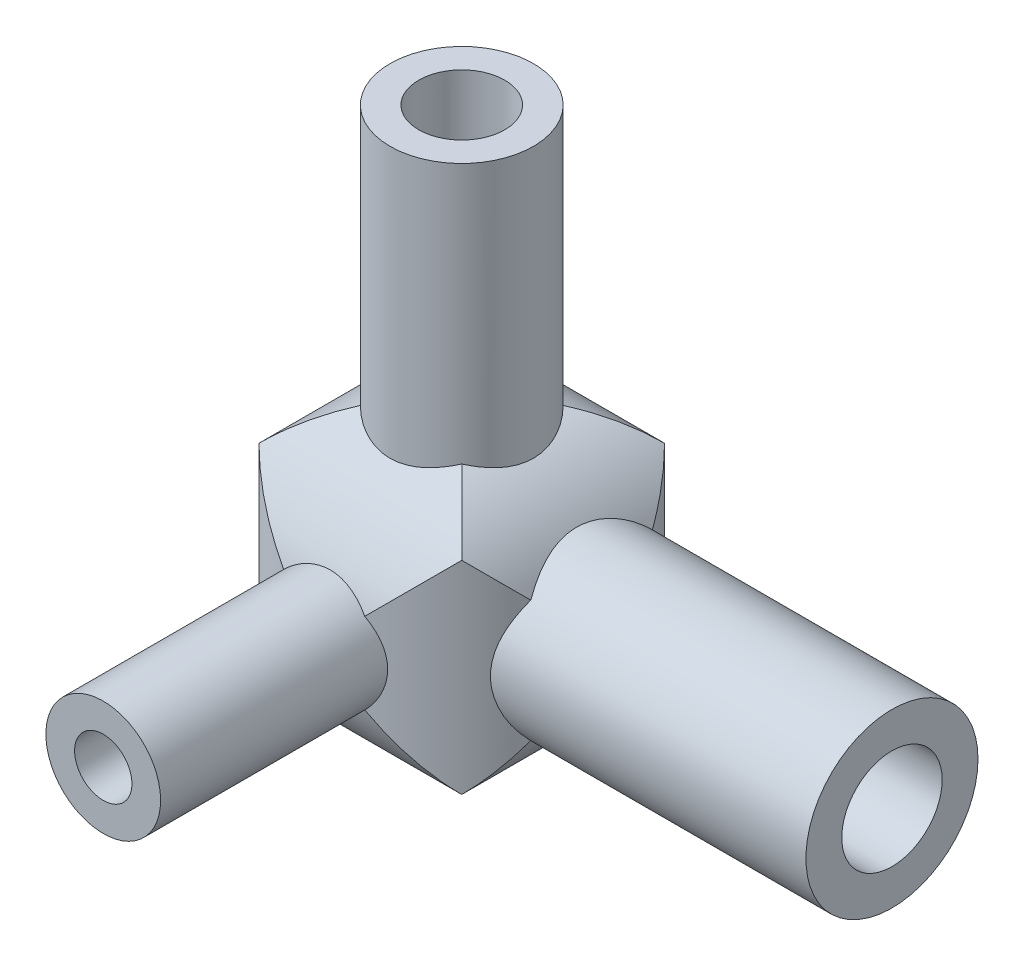
SolidWorks part; units mm, degrees
ref_plane "前视基准面" through (0, 0, 0) normal (0, 0, 1) x (1, 0, 0)
ref_plane "上视基准面" through (0, 0, 0) normal (0, 1, 0) x (1, 0, 0)
ref_plane "右视基准面" through (0, 0, 0) normal (1, 0, 0) x (0, 0, -1)
sketch3d "3D草图1"
  line L0 (-20, 0, 0) -> (20, 0, 0)
sweep "扫描2" add path "3D草图1" circular profile diameter 40 parameters "D3"=40
ref_plane "基准面1" through (0, -20, 0) normal (0, 1, 0) x (1, 0, 0)
sketch "草图2" plane through (0, -20, 0) normal (0, 1, 0) x (1, 0, 0)
  line L0 (-60, 60) -> (60, 60)
  line L1 (60, 60) -> (60, -60)
  line L2 (60, -60) -> (-60, -60)
  line L3 (-60, -60) -> (-60, 60)
  circle A0 centre (0, 0) radius 20
extrude "切除-拉伸1" cut sketch "草图2" along normal through all
ref_plane "基准面2" through (0, 0, -20) normal (0, 0, 1) x (1, 0, 0)
sketch "草图3" plane through (0, 0, -20) normal (0, 0, 1) x (1, 0, 0)
  line L0 (-60, -60) -> (60, -60)
  line L1 (60, -60) -> (60, 60)
  line L2 (60, 60) -> (-60, 60)
  line L3 (-60, 60) -> (-60, -60)
  circle A0 centre (0, 0) radius 20
extrude "切除-拉伸2" cut sketch "草图3" along normal through all
sketch3d "3D草图2"
  line L0 (-5, 0, 0) -> (60, 0, 0)
sweep "扫描4" add path "3D草图2" circular profile diameter 24 parameters "D3"=24
sketch3d "3D草图3"
  line L0 (0, -5, 0) -> (0, 55, 0)
sweep "扫描6" add path "3D草图3" circular profile diameter 20 parameters "D3"=20
sketch3d "3D草图4"
  line L0 (0, 0, -5) -> (0, 0, 50)
sweep "扫描8" add path "3D草图4" circular profile diameter 16 parameters "D3"=16
sketch3d "3D草图5"
  line L0 (2.8868, 2.8868, 2.8868) -> (-28.8675, -28.8675, -28.8675)
sweep "扫描10" add path "3D草图5" circular profile diameter 12 parameters "D3"=12
ref_plane "基准面3" through (0, 0, -28.8675) normal (0, 0, 1) x (1, 0, 0)
sketch "草图8" plane through (0, 0, -28.8675) normal (0, 0, 1) x (1, 0, 0)
  line L0 (-33.1102, -33.1102) -> (-24.6249, -24.6249) construction
  line L1 (-33.1102, -33.1102) -> (-24.6249, -24.6249)
  arc A0 (-24.6249, -24.6249) -> (-33.1102, -33.1102) centre (-28.8675, -28.8675) cw
revolve "旋转1" add sketch "草图8" angle 360 about L0
ref_plane "基准面4" through (60, 0, 0) normal (1, 0, 0) x (0, 0, -1)
sketch "草图9" plane through (60, 0, 0) normal (1, 0, 0) x (0, 0, -1)
  circle A0 centre (0, 0) radius 7
extrude "切除-拉伸3" cut sketch "草图9" against normal blind 65
ref_plane "基准面5" through (0, 55, 0) normal (0, 1, 0) x (1, 0, 0)
sketch "草图10" plane through (0, 55, 0) normal (0, 1, 0) x (1, 0, 0)
  circle A0 centre (0, 0) radius 6
extrude "切除-拉伸4" cut sketch "草图10" against normal blind 60
ref_plane "基准面6" through (0, 0, 50) normal (0, 0, 1) x (1, 0, 0)
sketch "草图11" plane through (0, 0, 50) normal (0, 0, 1) x (1, 0, 0)
  circle A0 centre (0, 0) radius 4
extrude "切除-拉伸5" cut sketch "草图11" against normal blind 55
